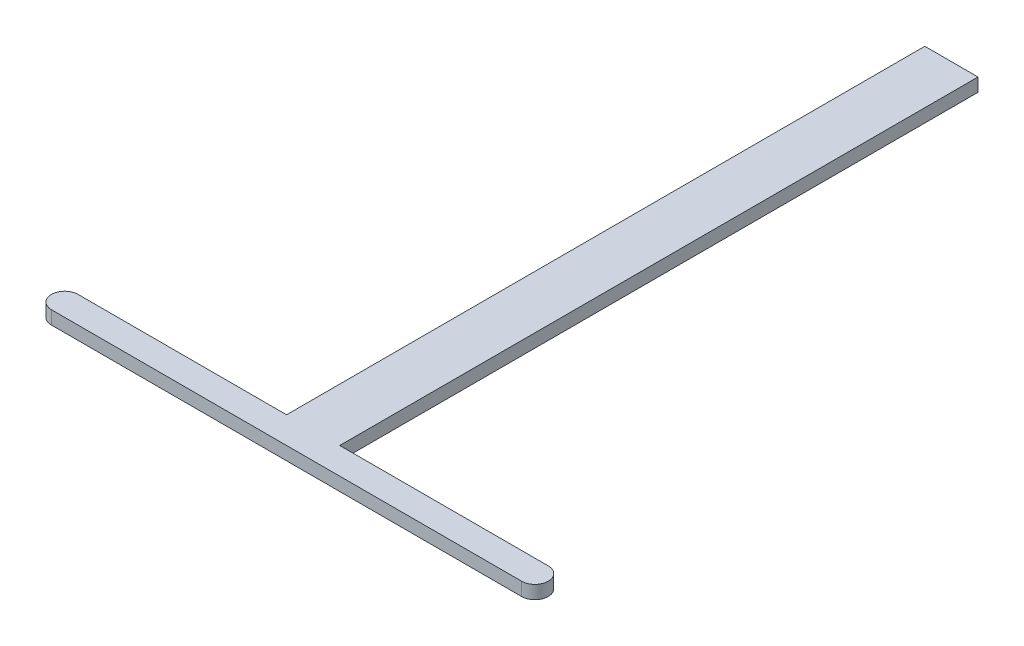
SolidWorks part; units mm, degrees
ref_plane "Front Plane" through (0, 0, 0) normal (0, 0, 1) x (1, 0, 0)
ref_plane "Top Plane" through (0, 0, 0) normal (0, 1, 0) x (1, 0, 0)
ref_plane "Right Plane" through (0, 0, 0) normal (1, 0, 0) x (0, 0, -1)
sketch "Sketch1" plane through (0, 0, 0) normal (0, 1, 0) x (1, 0, 0)
  line L0 (-6.35, 0) -> (-56.134, 0)
  line L1 (-6.35, 152.4) -> (6.35, 152.4)
  line L2 (-6.35, 152.4) -> (-6.35, 0)
  line L4 (6.35, 152.4) -> (6.35, 0)
  line L5 (56.134, 0) -> (6.35, 0)
  line L7 (56.134, -6.35) -> (-56.134, -6.35)
  arc A0 (-56.134, 0) -> (-56.134, -6.35) centre (-56.134, -3.175) ccw
  arc A1 (56.134, -6.35) -> (56.134, 0) centre (56.134, -3.175) ccw
  dimension "D4" = 6.35
  dimension "D5" = 6.35
  dimension "D2" = 12.7
  dimension "D3" = 6.35
extrude "Boss-Extrude1" add sketch "Sketch1" along normal blind 3.175
